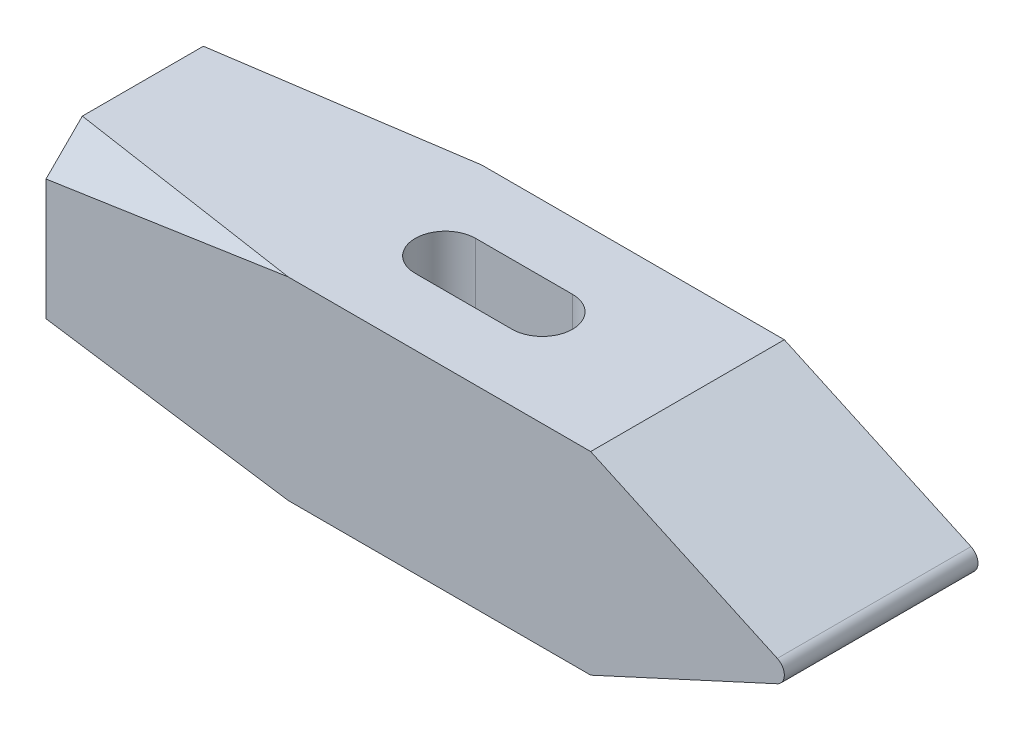
SolidWorks part; units mm, degrees
ref_plane "Front Plane" through (0, 0, 0) normal (0, 0, 1) x (1, 0, 0)
ref_plane "Top Plane" through (0, 0, 0) normal (0, 1, 0) x (1, 0, 0)
ref_plane "Right Plane" through (0, 0, 0) normal (1, 0, 0) x (0, 0, -1)
sketch "Sketch1" plane through (0, 0, 0) normal (0, 0, 1) x (1, 0, 0)
  line L0 (0, 16) -> (0, -16)
  line L1 (0, -16) -> (90, -16)
  line L2 (90, -16) -> (120.8357, -1.817)
  line L3 (120.8357, 1.817) -> (90, 16)
  line L4 (90, 16) -> (0, 16)
  line L5 (15.3896, 0) -> (40.9368, 0) construction
  arc A0 (120.8357, -1.817) -> (120.8357, 1.817) centre (120, 0) ccw
  dimension "D4" = 2
  dimension "D1" = 90
  dimension "D2" = 32
  dimension "D3" = 16
  dimension "D5" = 30
extrude "Boss-Extrude1" add sketch "Sketch1" along normal blind 32
sketch "Sketch2" plane through (0, 16, 0) normal (0, 1, 0) x (1, 0, 0)
  line L0 (50, -16) -> (66, -16) construction
  line L1 (50, -11) -> (66, -11)
  line L2 (50, -21) -> (66, -21)
  line L3 (0, -32) -> (0, 0) construction
  line L4 (90, -32) -> (0, -32) construction
  arc A0 (50, -11) -> (50, -21) centre (50, -16) ccw
  arc A1 (66, -21) -> (66, -11) centre (66, -16) ccw
  point P2 (58, -16)
  point P7 (0, 0)
  dimension "D1" = 5
  dimension "D2" = 16
  dimension "D3" = 50
  dimension "D4" = 16
extrude "Cut-Extrude1" cut sketch "Sketch2" against normal blind 32
sketch "Sketch3" plane through (0, 0, 0) normal (-1, 0, 0) x (0, 0, 1)
  line L0 (32, 16) -> (0, 16) construction
  line L1 (32, 16) -> (32, -16) construction
  point P0 (26, 16)
  point P1 (32, 10)
  dimension "D1" = 6
  dimension "D2" = 6
sketch "Sketch4" plane through (0, 0, 32) normal (0, 0, 1) x (1, 0, 0)
  line L0 (90, 16) -> (0, 16) construction
  point P0 (40, 16)
  dimension "D1" = 40
ref_plane "Plane1" through (-3.115, 20.7664, 20.7664) normal (-0.1055, 0.7032, 0.7032) x (0.9944, 0.0746, 0.0746)
sketch "Sketch5" plane through (-3.115, 20.7664, 20.7664) normal (-0.1055, 0.7032, 0.7032) x (0.9944, 0.0746, 0.0746)
  line L0 (43.3568, -11.3137) -> (3.1324, -7.0711)
  line L1 (3.1324, -7.0711) -> (3.1324, -15.5563)
  line L2 (3.1324, -15.5563) -> (43.3568, -11.3137)
extrude "Cut-Extrude2" cut sketch "Sketch5" along normal blind 32 contours L1 L2 L0
sketch "Sketch8" plane through (0, 0, 0) normal (-1, 0, 0) x (0, 0, 1)
  line L0 (0, 16) -> (0, -16) construction
  line L1 (26, 16) -> (0, 16) construction
  line L2 (32, -16) -> (0, -16) construction
  line L3 (32, 10) -> (32, -16) construction
  point P0 (0, 10)
  point P1 (6, 16)
  point P4 (0, -10)
  point P7 (6, -16)
  point P8 (32, -10)
  point P11 (26, -16)
  dimension "D1" = 6
  dimension "D2" = 6
  dimension "D3" = 6
  dimension "D4" = 6
  dimension "D5" = 6
  dimension "D6" = 6
sketch "Sketch9" plane through (0, 16, 0) normal (0, 1, 0) x (1, 0, 0)
  line L0 (90, 0) -> (0, 0) construction
  point P0 (40, 0)
  dimension "D1" = 40
sketch "Sketch10" plane through (0, -16, 0) normal (0, -1, 0) x (-1, 0, 0)
  point P0 (-40, -32)
  point P1 (-40, 0)
ref_plane "Plane2" through (-3.115, -20.7664, 20.7664) normal (-0.1055, -0.7032, 0.7032) x (0.9944, -0.0746, 0.0746)
sketch "Sketch11" plane through (-3.115, -20.7664, 20.7664) normal (-0.1055, -0.7032, 0.7032) x (0.9944, -0.0746, 0.0746)
  line L0 (43.3568, 11.3137) -> (3.1324, 15.5563)
  line L1 (3.1324, 15.5563) -> (3.1324, 7.0711)
  line L2 (3.1324, 7.0711) -> (43.3568, 11.3137)
extrude "Cut-Extrude3" cut sketch "Sketch11" along normal blind 32
ref_plane "Plane3" through (-0.7417, -4.9444, -4.9444) normal (-0.1055, -0.7032, -0.7032) x (-0.9944, 0.0746, 0.0746)
sketch "Sketch12" plane through (-0.7417, -4.9444, -4.9444) normal (-0.1055, -0.7032, -0.7032) x (-0.9944, 0.0746, 0.0746)
  line L0 (-40.9702, -11.3137) -> (-0.7458, -7.0711)
  line L1 (-0.7458, -7.0711) -> (-0.7458, -15.5563)
  line L2 (-0.7458, -15.5563) -> (-40.9702, -11.3137)
extrude "Cut-Extrude5" cut sketch "Sketch12" along normal blind 32
ref_plane "Plane4" through (-0.7417, 4.9444, -4.9444) normal (0.1055, -0.7032, 0.7032) x (0.9944, 0.0746, -0.0746)
sketch "Sketch13" plane through (-0.7417, 4.9444, -4.9444) normal (0.1055, -0.7032, 0.7032) x (0.9944, 0.0746, -0.0746)
  line L0 (40.9702, 11.3137) -> (0.7458, 7.0711)
  line L1 (0.7458, 7.0711) -> (0.7458, 15.5563)
  line L2 (0.7458, 15.5563) -> (40.9702, 11.3137)
extrude "Cut-Extrude6" cut sketch "Sketch13" against normal blind 32
